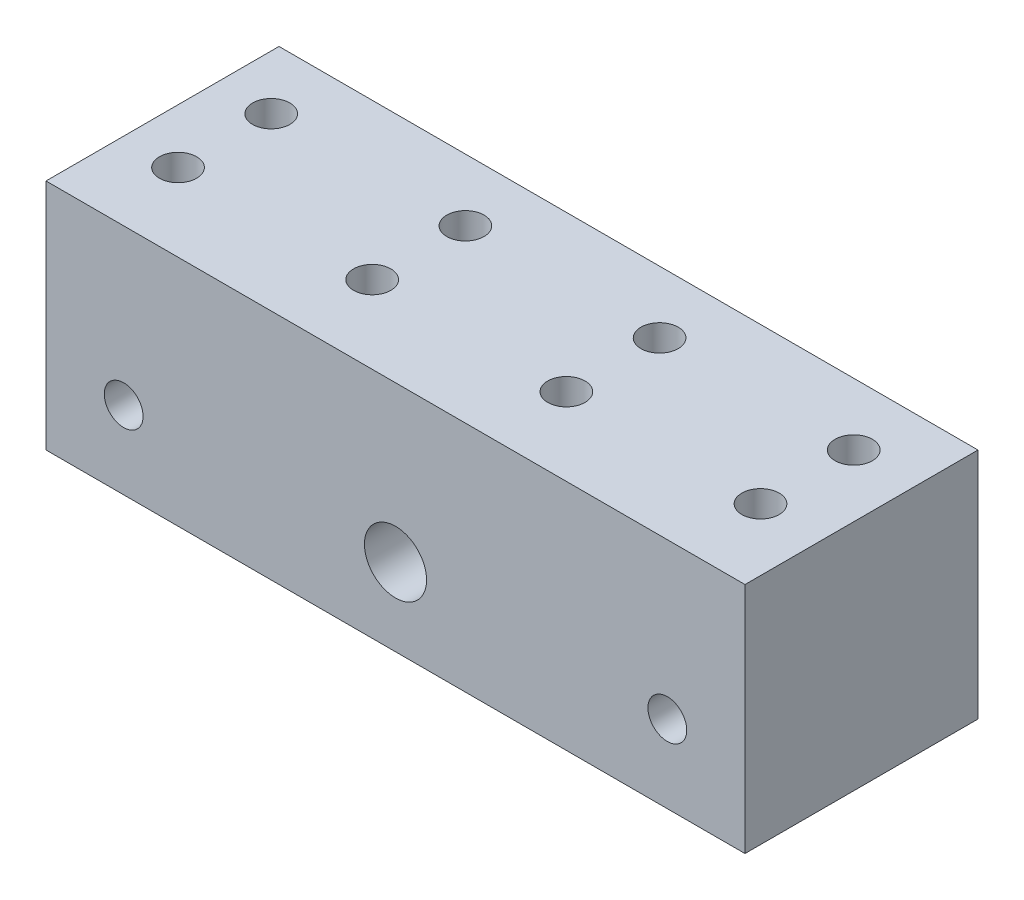
SolidWorks part; units mm, degrees
ref_plane "Front Plane" through (0, 0, 0) normal (0, 0, 1) x (1, 0, 0)
ref_plane "Top Plane" through (0, 0, 0) normal (0, 1, 0) x (1, 0, 0)
ref_plane "Right Plane" through (0, 0, 0) normal (1, 0, 0) x (0, 0, -1)
sketch "Sketch1" plane through (0, 0, 0) normal (0, 0, 1) x (1, 0, 0)
  line L1 (0, 0) -> (90, 0)
  line L2 (0, 0) -> (0, 30)
  line L3 (0, 30) -> (90, 30)
  line L4 (90, 0) -> (90, 30)
  circle A0 centre (10, 10) radius 2.5
  circle A1 centre (45, 10) radius 4
  circle A2 centre (80, 10) radius 2.5
  point P11 (0, 0)
  point P13 (45, 30)
  dimension "D3" = 5
  dimension "D6" = 10
  dimension "D7" = 8
  dimension "D1" = 90
  dimension "D2" = 30
  dimension "D4" = 10
  dimension "D5" = 10
extrude "Boss-Extrude1" add sketch "Sketch1" along normal blind 30
sketch "Sketch4" plane through (0, 30, 0) normal (0, 1, 0) x (1, 0, 0)
  line L0 (90, 0) -> (0, 0) construction
  line L1 (0, -30) -> (0, 0) construction
  circle A0 centre (7, -8) radius 2.4
  circle A2 centre (32, -8) radius 2.4
  circle A3 centre (57, -8) radius 2.4
  circle A4 centre (82, -8) radius 2.4
  circle A5 centre (32, -20) radius 2.4
  circle A6 centre (57, -20) radius 2.4
  circle A7 centre (82, -20) radius 2.4
  circle A8 centre (7, -20) radius 2.4
  dimension "D2" = 7
  dimension "D3" = 4.8
  dimension "D1" = 8
  dimension "D6" = 25
  dimension "D7" = 12
  dimension "D4" = 4
  dimension "D5" = 2
extrude "Cut-Extrude1" cut sketch "Sketch4" against normal blind 5
